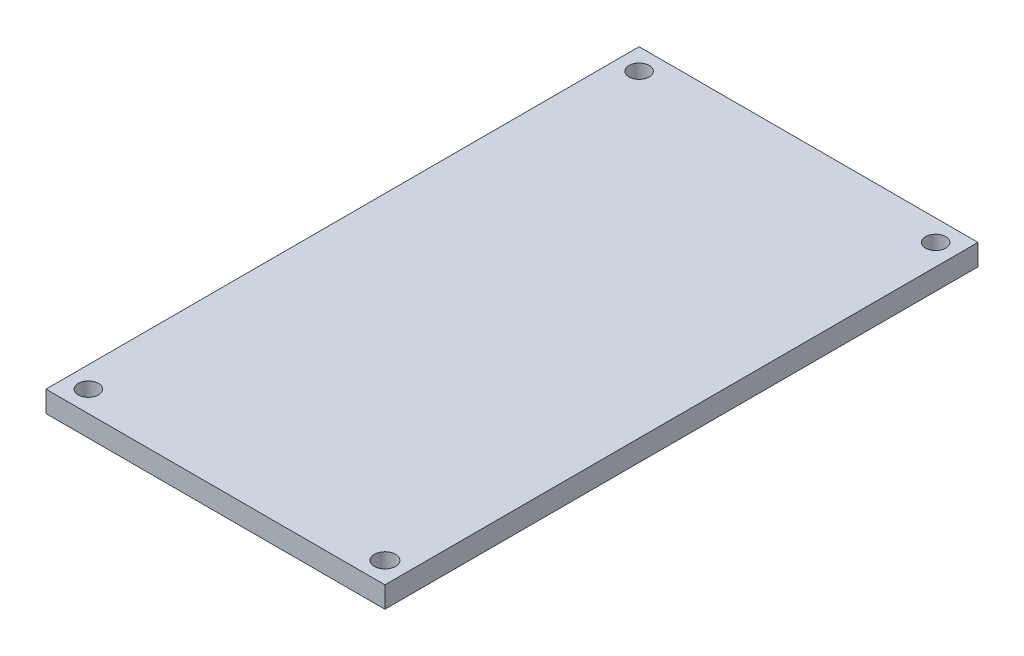
SolidWorks part; units mm, degrees
ref_plane "前视基准面" through (0, 0, 0) normal (0, 0, 1) x (1, 0, 0)
ref_plane "上视基准面" through (0, 0, 0) normal (0, 1, 0) x (1, 0, 0)
ref_plane "右视基准面" through (0, 0, 0) normal (1, 0, 0) x (0, 0, -1)
other "Configuration Table"
sketch "草图2" plane through (0, 0, 0) normal (0, 1, 0) x (1, 0, 0)
  line L1 (16, -28) -> (-16, -28)
  line L2 (16, -28) -> (16, 28)
  line L3 (16, 28) -> (-16, 28)
  line L4 (-16, -28) -> (-16, 28)
  line L5 (16, -28) -> (-16, 28) construction
  line L6 (16, 28) -> (-16, -28) construction
  circle A0 centre (-14, 26) radius 0.95
  circle A1 centre (14, 26) radius 0.95
  circle A2 centre (-14, -26) radius 0.95
  circle A3 centre (14, -26) radius 1
  point P0 (0, 0)
  dimension "D3" = 1.9
  dimension "D6" = 1.9
  dimension "D9" = 1.9
  dimension "D12" = 2
  dimension "D1" = 32
  dimension "D2" = 56
  dimension "D4" = 2
  dimension "D5" = 2
  dimension "D7" = 2
  dimension "D8" = 2
  dimension "D10" = 2
  dimension "D11" = 2
  dimension "D13" = 2
  dimension "D14" = 2
extrude "凸台-拉伸2" add sketch "草图2" along normal blind 2
